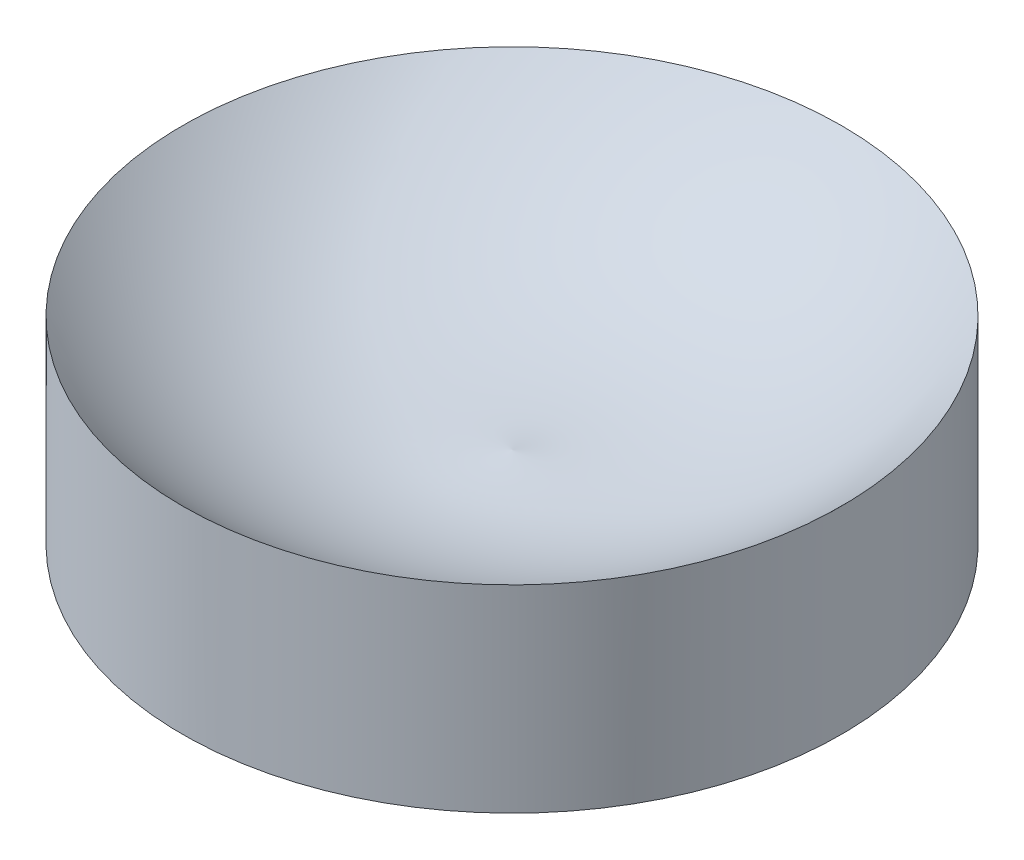
SolidWorks part; units mm, degrees
ref_plane "Front Plane" through (0, 0, 0) normal (0, 0, 1) x (1, 0, 0)
ref_plane "Top Plane" through (0, 0, 0) normal (0, 1, 0) x (1, 0, 0)
ref_plane "Right Plane" through (0, 0, 0) normal (1, 0, 0) x (0, 0, -1)
sketch "Sketch1" plane through (0, 0, 0) normal (1, 0, 0) x (0, 0, -1)
  line L0 (0, 0) -> (-5, 0)
  line L1 (-5, 0) -> (-5, 3)
  line L2 (0, 0) -> (0, 1.2379)
  spline S0 degree 2 poles (-5, 3) (-2.9077, 0.8846) (0, 1.2379) knots 0 0 0 1 1 1
  dimension "D1" = 5
  dimension "D2" = 3
revolve "Revolve1" add sketch "Sketch1" angle 360 about L2
